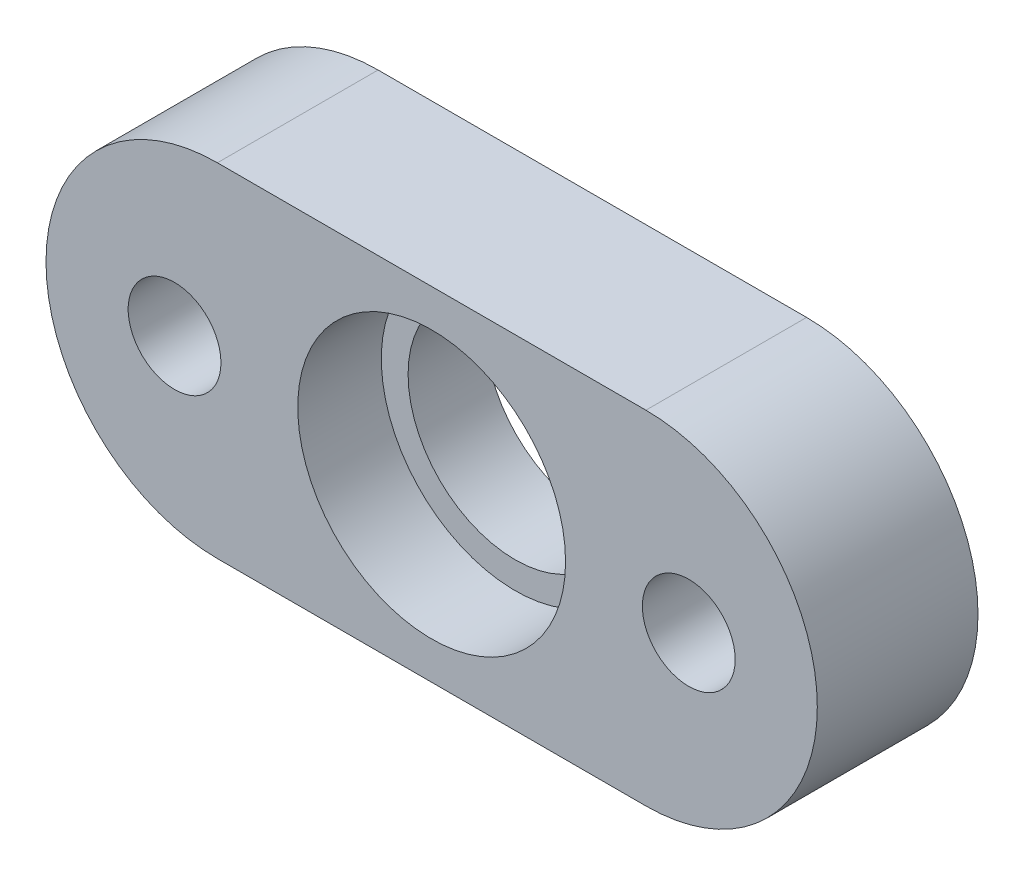
SolidWorks part; units mm, degrees
ref_plane "Front Plane" through (0, 0, 0) normal (0, 0, 1) x (1, 0, 0)
ref_plane "Top Plane" through (0, 0, 0) normal (0, 1, 0) x (1, 0, 0)
ref_plane "Right Plane" through (0, 0, 0) normal (1, 0, 0) x (0, 0, -1)
sketch "Sketch2" plane through (0, 0, 0) normal (0, 0, 1) x (1, 0, 0)
  line L0 (-12.7, 0) -> (12.7, 0) construction
  line L1 (-12.7, 10.16) -> (12.7, 10.16)
  line L2 (-12.7, -10.16) -> (12.7, -10.16)
  arc A0 (-12.7, 10.16) -> (-12.7, -10.16) centre (-12.7, 0) ccw
  arc A1 (12.7, -10.16) -> (12.7, 10.16) centre (12.7, 0) ccw
  point P2 (0, 0)
  dimension "D2" = 10.16
  dimension "D1" = 25.4
extrude "Boss-Extrude5" add sketch "Sketch2" along normal blind 9.525
sketch "Sketch5" plane through (0, 0, 9.525) normal (0, 0, 1) x (1, 0, 0)
  circle A0 centre (0, 0) radius 7.9375
  dimension "D1" = 15.875
extrude "Cut-Extrude3" cut sketch "Sketch5" against normal blind 4.953
sketch "Sketch6" plane through (0, 0, 9.525) normal (0, 0, 1) x (1, 0, 0)
  line L0 (-22.86, 0) -> (22.86, 0) construction
  line L1 (0, 10.16) -> (0, -10.16) construction
  line L2 (12.7, 10.16) -> (-12.7, 10.16) construction
  line L3 (-12.7, -10.16) -> (12.7, -10.16) construction
  circle A0 centre (0, 0) radius 6.35
  arc A1 (-12.7, 10.16) -> (-12.7, -10.16) centre (-12.7, 0) ccw construction
  arc A2 (12.7, -10.16) -> (12.7, 10.16) centre (12.7, 0) ccw construction
  circle A3 centre (-15.24, 0) radius 2.75
  circle A4 centre (15.24, 0) radius 2.75
  dimension "D1" = 12.7
  dimension "D2" = 5.5
  dimension "D3" = 30.48
extrude "Cut-Extrude4" cut sketch "Sketch6" against normal through all
